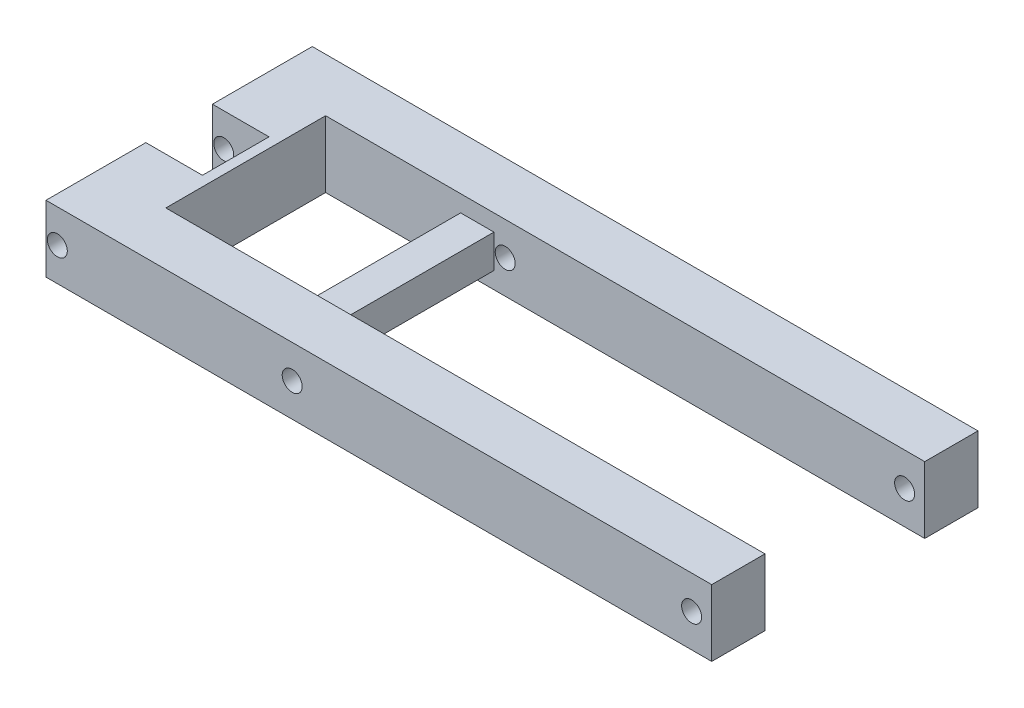
SolidWorks part; units mm, degrees
ref_plane "Piano frontale" through (0, 0, 0) normal (0, 0, 1) x (1, 0, 0)
ref_plane "Piano superiore" through (0, 0, 0) normal (0, 1, 0) x (1, 0, 0)
ref_plane "Piano destro" through (0, 0, 0) normal (1, 0, 0) x (0, 0, -1)
sketch "Schizzo1" plane through (0, 0, 0) normal (0, 1, 0) x (1, 0, 0)
  line L0 (0, 0) -> (-410.3417, 0) construction
  line L1 (0, 0) -> (510.4978, 0) construction
  line L5 (-332.8468, -200) -> (-332.8468, 200)
  line L7 (-332.8468, 200) -> (667.1532, 200)
  line L8 (667.1532, 200) -> (667.1532, 120)
  line L9 (667.1532, 120) -> (-232.8468, 120)
  line L10 (-232.8468, 120) -> (-232.8468, -120)
  line L11 (667.1532, -120) -> (-232.8468, -120)
  line L12 (667.1532, -200) -> (667.1532, -120)
  line L13 (-332.8468, -200) -> (667.1532, -200)
  point P11 (-232.8468, 0)
  point P14 (-332.8468, 0)
  dimension "D1" = 1000
  dimension "D2" = 100
  dimension "D4" = 232.8468
  dimension "D3" = 80
  dimension "D5" = 120
extrude "Estrusione-Estrusione1" add sketch "Schizzo1" along normal blind 100
sketch "Schizzo2" plane through (0, 0, 0) normal (0, 0, 1) x (1, 0, 0)
  line L0 (-332.8468, 50) -> (667.1532, 50) construction
  line L8 (-332.8468, 100) -> (-332.8468, 0) construction
  line L13 (667.1532, 100) -> (667.1532, 0) construction
  circle A7 centre (-315.8468, 50) radius 15
  circle A8 centre (36.9532, 50) radius 15
  circle A9 centre (636.9532, 50) radius 15
  dimension "D1" = 30
  dimension "D2" = 30
  dimension "D3" = 30
  dimension "D4" = 352.8
  dimension "D5" = 600
  dimension "D6" = 17
extrude "Taglio-Estrusione5" cut sketch "Schizzo2" against normal through all both and the other way through all
sketch "Schizzo3" plane through (0, 0, 0) normal (0, 1, 0) x (1, 0, 0)
  line L0 (-14.9222, 0) -> (-32.6568, 0) construction
  line L1 (-332.8468, -50) -> (-332.8468, 50)
  line L2 (-332.8468, 50) -> (-247.8468, 50)
  line L3 (-247.8468, 50) -> (-247.8468, -50)
  line L4 (667.1532, -120) -> (-232.8468, -120)
  line L5 (667.1532, -120) -> (-232.8468, -120)
  line L6 (-232.8468, -120) -> (-232.8468, 120)
  line L7 (-232.8468, -120) -> (-232.8468, 120)
  line L13 (-332.8468, -50) -> (-247.8468, -50)
  line L21 (-232.8468, 120) -> (667.1532, 120)
  line L22 (-232.8468, 120) -> (667.1532, 120)
  line L23 (667.1532, 120) -> (667.1532, 200)
  line L24 (667.1532, 120) -> (667.1532, 200)
  line L25 (667.1532, 200) -> (-332.8468, 200)
  line L26 (667.1532, 200) -> (-332.8468, 200)
  line L27 (-332.8468, 200) -> (-332.8468, -200)
  line L28 (-332.8468, 200) -> (-332.8468, -200)
  line L29 (-332.8468, -200) -> (667.1532, -200)
  line L30 (-332.8468, -200) -> (667.1532, -200)
  line L31 (667.1532, -200) -> (667.1532, -120)
  line L32 (667.1532, -200) -> (667.1532, -120)
  point P21 (-247.8468, 0)
  point P22 (-332.8468, 0)
  dimension "D2" = 85
  dimension "D3" = 0
  dimension "D4" = 50
  dimension "D1" = 0
extrude "Taglio-Estrusione6" cut sketch "Schizzo3" along normal through all both contours L3 L13 L1 L2
sketch "Schizzo4" plane through (0, 0, 0) normal (0, 0, 1) x (1, 0, 0)
  line L0 (-30, 75) -> (20, 75)
  line L1 (20, 75) -> (20, 25)
  line L2 (20, 25) -> (-30, 25)
  line L3 (-30, 25) -> (-30, 75)
  line L4 (-332.8468, 0) -> (667.1532, 0) construction
  line L5 (-332.8468, 100) -> (667.1532, 100) construction
  dimension "D1" = 25
  dimension "D2" = 25
  dimension "D3" = 20
  dimension "D4" = 50
extrude "Estrusione-Estrusione2" add sketch "Schizzo4" along normal up to next and the other way up to next
